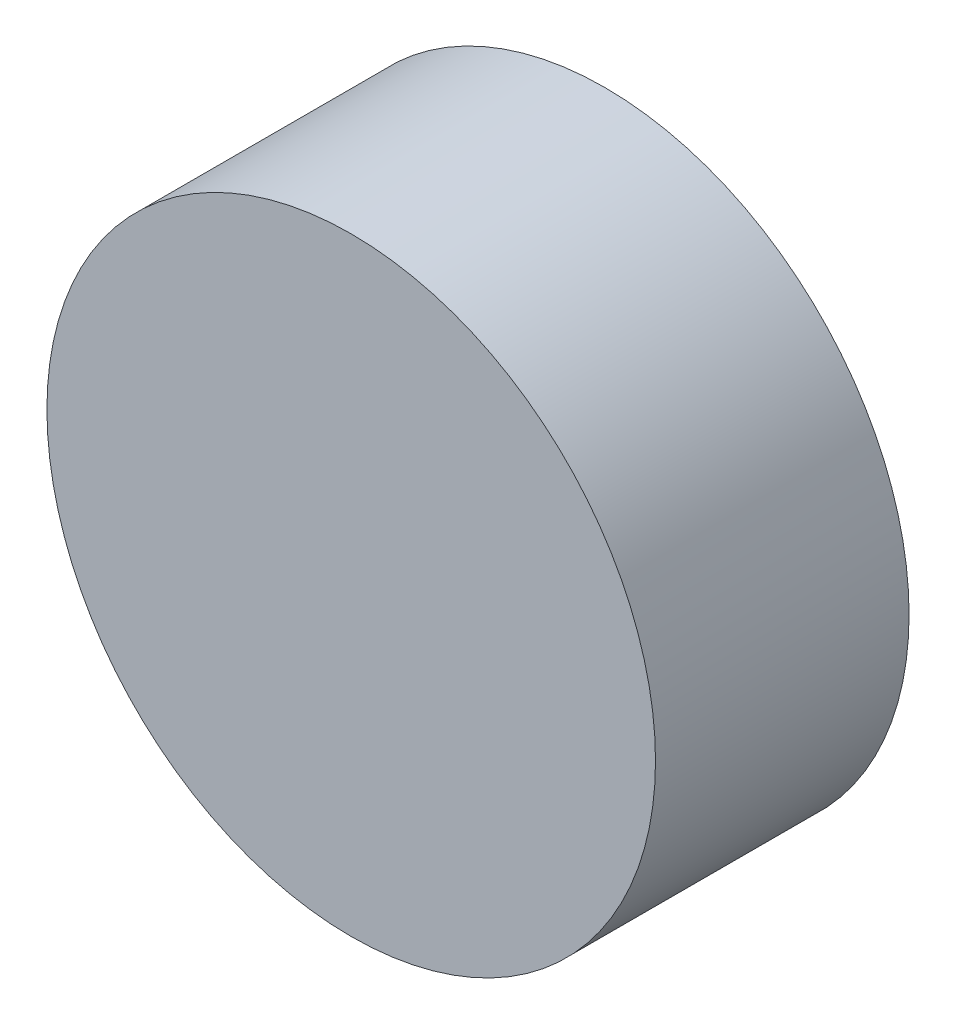
SolidWorks part; units mm, degrees
ref_plane "Front Plane" through (0, 0, 0) normal (0, 0, 1) x (1, 0, 0)
ref_plane "Top Plane" through (0, 0, 0) normal (0, 1, 0) x (1, 0, 0)
ref_plane "Right Plane" through (0, 0, 0) normal (1, 0, 0) x (0, 0, -1)
sketch "Sketch1" plane through (0, 0, 0) normal (0, 0, 1) x (1, 0, 0)
  circle A0 centre (0, 0) radius 3
  point P3 (0, 0)
extrude "Magnet" add sketch "Sketch1" along normal blind 2.5 contours A0
